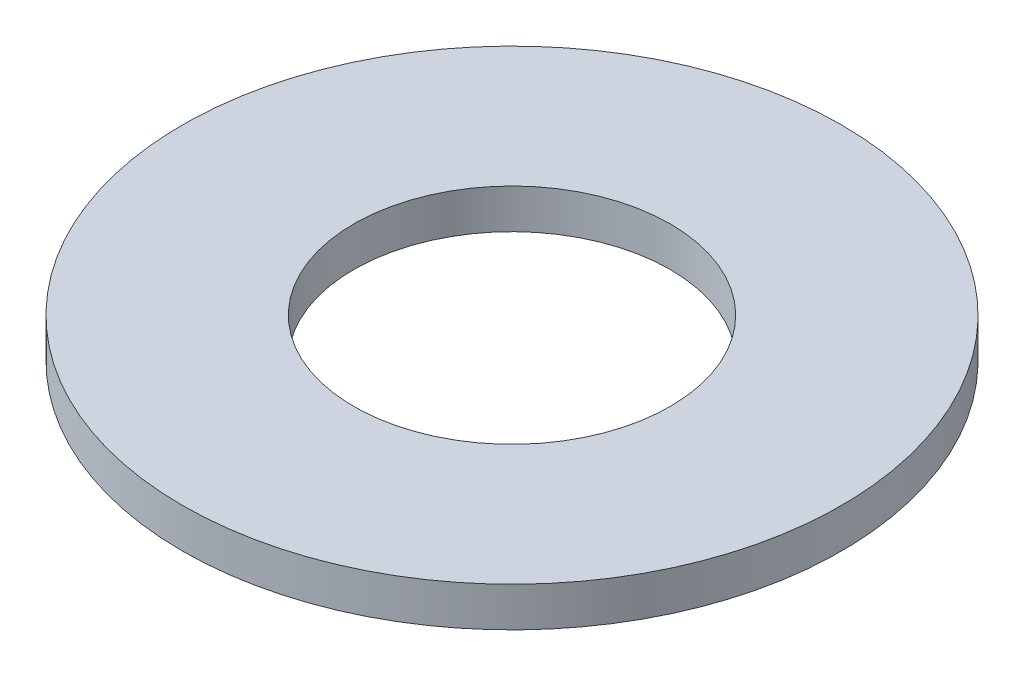
SolidWorks part; units mm, degrees
material "钢"
ref_plane "基准面1" through (0, 0, 0) normal (0, 0, 1) x (1, 0, 0)
ref_plane "基准面2" through (0, 0, 0) normal (0, 1, 0) x (1, 0, 0)
ref_plane "基准面3" through (0, 0, 0) normal (1, 0, 0) x (0, 0, -1)
sketch "尺寸草图" plane through (0, 0, 0) normal (0, 0, 1) x (1, 0, 0)
  line L0 (0, 0) -> (9.1, 0)
  point P3 (0.3, 0)
  point P4 (5, 0)
  point P5 (2.4, 0)
  dimension "h" = 0.3
  dimension "d2" = 5
  dimension "d1" = 2.4
sketch "草图1" plane through (0, 0, 0) normal (0, 0, 1) x (1, 0, 0)
  line L0 (0, 0) -> (0, 52.7318) construction
  line L2 (-1.2, 8.6445) -> (-2.5, 8.6445)
  line L3 (-1.2, 8.6445) -> (-1.2, 8.9445)
  line L4 (-1.2, 8.9445) -> (-2.5, 8.9445)
  line L5 (-2.5, 8.6445) -> (-2.5, 8.9445)
  dimension "h" = 0.3
  dimension "D1" = 1.2
  dimension "D2" = 2.5
revolve "基体-旋转" add sketch "草图1" angle 360 about L0
equation "\"h@草图1\" = \"h@尺寸草图\""
equation "\"D1@草图1\" = \"d1@尺寸草图\" / 2"
equation "\"D2@草图1\" = \"d2@尺寸草图\" / 2"
